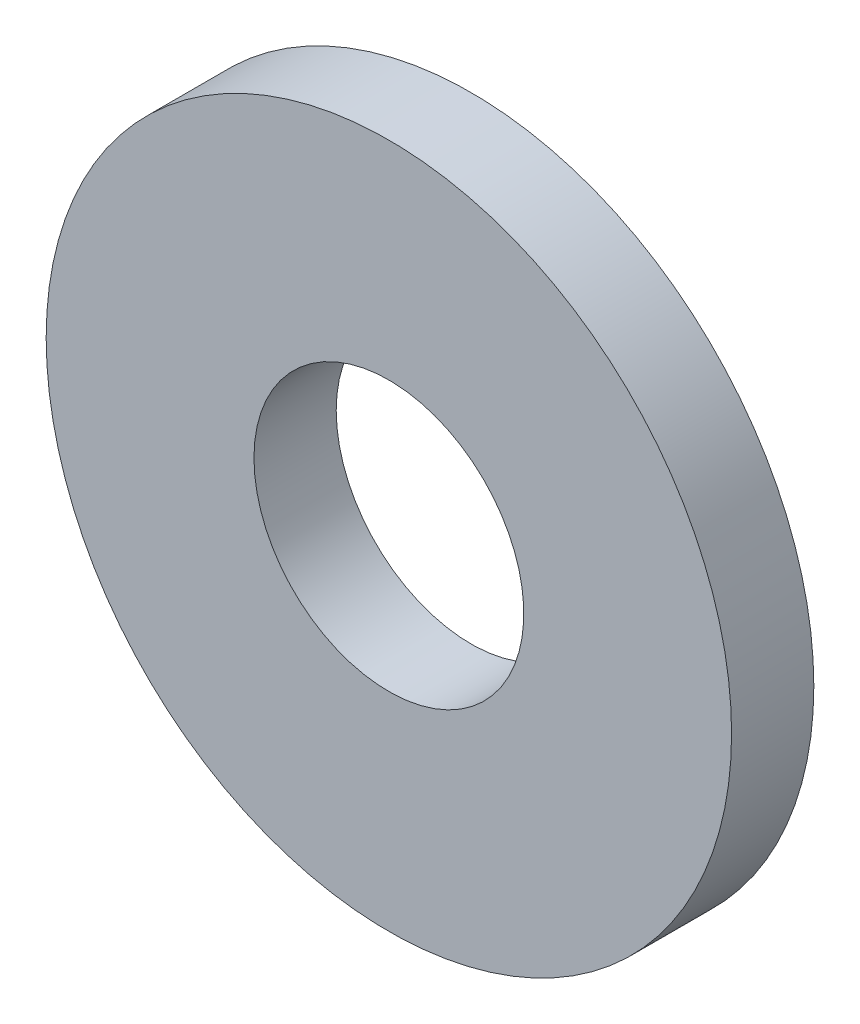
SolidWorks part; units mm, degrees
material "Nylon 6/10"
ref_plane "Front Plane" through (0, 0, 0) normal (0, 0, 1) x (1, 0, 0)
ref_plane "Top Plane" through (0, 0, 0) normal (0, 1, 0) x (1, 0, 0)
ref_plane "Right Plane" through (0, 0, 0) normal (1, 0, 0) x (0, 0, -1)
sketch "Sketch1" plane through (0, 0, 0) normal (0, 0, 1) x (1, 0, 0)
  circle A0 centre (0, 0) radius 6.35
  circle A1 centre (0, 0) radius 2.5
  dimension "D1" = 5
  dimension "D2" = 12.7
extrude "Boss-Extrude1" add sketch "Sketch1" along normal blind 1.524
